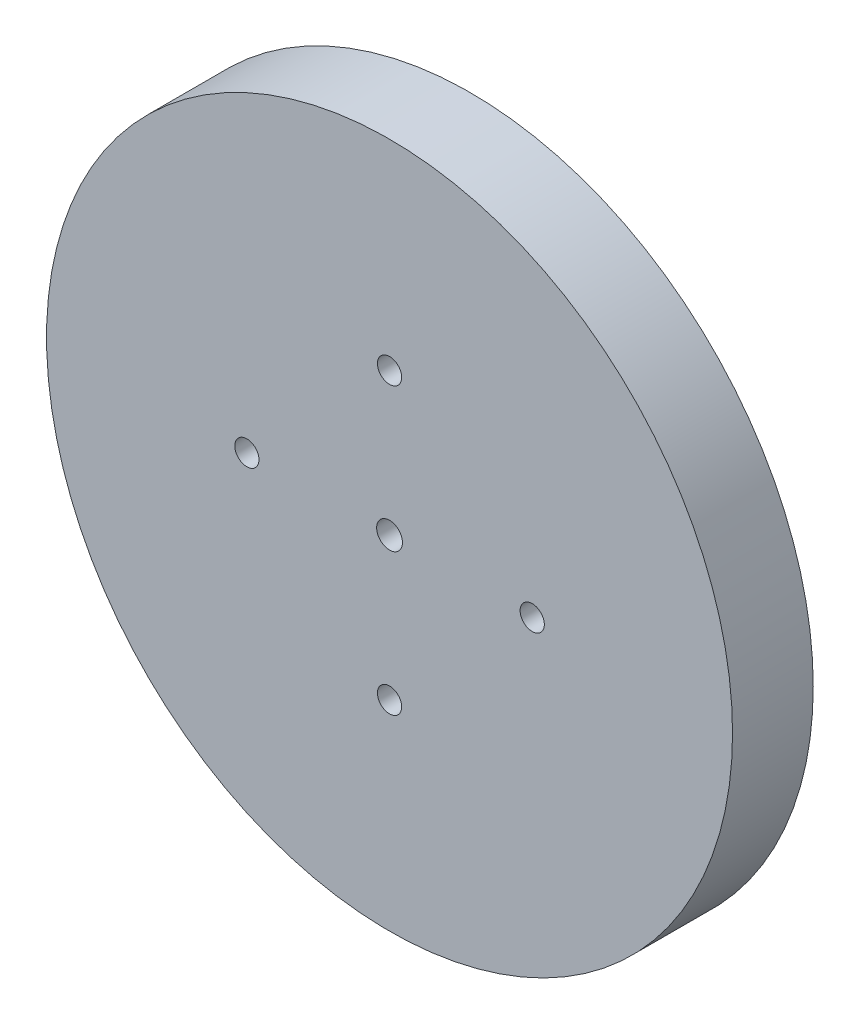
SolidWorks part; units mm, degrees
ref_plane "前视基准面" through (0, 0, 0) normal (0, 0, 1) x (1, 0, 0)
ref_plane "上视基准面" through (0, 0, 0) normal (0, 1, 0) x (1, 0, 0)
ref_plane "右视基准面" through (0, 0, 0) normal (1, 0, 0) x (0, 0, -1)
sketch "草图1" plane through (0, 0, 0) normal (0, 0, 1) x (1, 0, 0)
  circle A0 centre (0, 0) radius 42.5
  dimension "D1" = 85
extrude "凸台-拉伸1" add sketch "草图1" along normal blind 10
sketch "草图2" plane through (0, 0, 0) normal (0, 0, -1) x (-1, 0, 0)
  circle A0 centre (0, 0) radius 39.5
  dimension "D1" = 79
extrude "切除-拉伸1" cut sketch "草图2" against normal blind 7
sketch "草图4" plane through (0, 0, 10) normal (0, 0, 1) x (1, 0, 0)
  line L0 (-60.9278, 0) -> (72.5662, 0) construction
  line L1 (0, 46.9988) -> (0, -55.6743) construction
  line L2 (-17.6777, 0) -> (0, -17.6777)
  line L3 (0, 17.6777) -> (17.6777, 0)
  line L4 (0, -17.6777) -> (17.6777, 0)
  line L5 (-17.6777, 0) -> (0, 17.6777)
  circle A0 centre (0, 17.6777) radius 1.5
  circle A1 centre (17.6777, 0) radius 1.5
  circle A2 centre (0, -17.6777) radius 1.5
  circle A3 centre (-17.6777, 0) radius 1.5
  circle A4 centre (0, 0) radius 1.6
  dimension "D1" = 3
  dimension "D2" = 25
  dimension "D3" = 3.2
  dimension "D4" = 25
  dimension "D5" = 90
extrude "切除-拉伸2" cut sketch "草图4" against normal through all contours A2 | A1 | A0 | A3 | A4
sketch "草图5" plane through (0, 0, 0) normal (0, 1, 0) x (1, 0, 0)
  line L0 (-62.1612, 0) -> (59.7389, 0) construction
  line L1 (0, 35.1102) -> (0, -46.694) construction
  line L2 (40.2727, 0) -> (41.7273, 0)
  arc A1 (40.2727, 0) -> (41.7273, 0) centre (41, 0.3333) ccw
  dimension "D2" = 0.8
  dimension "D1" = 41
revolve "切除-旋转1" cut sketch "草图5" angle 360 about L1
